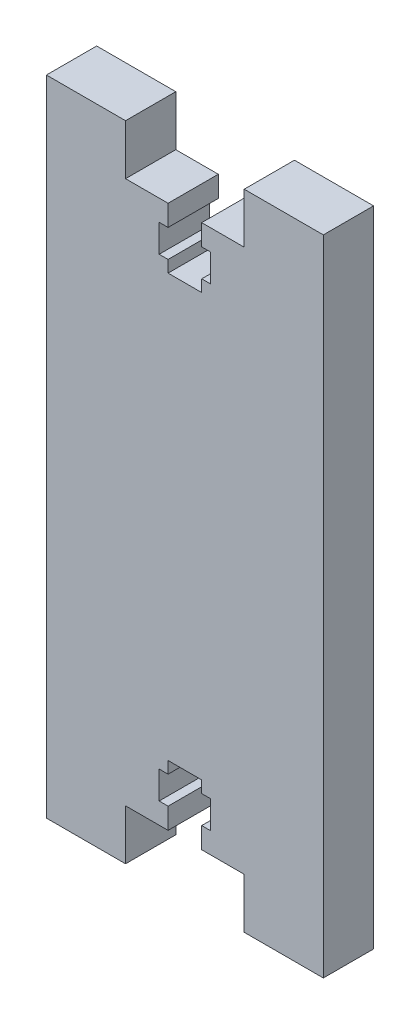
SolidWorks part; units mm, degrees
ref_plane "Front Plane" through (0, 0, 0) normal (0, 0, 1) x (1, 0, 0)
ref_plane "Top Plane" through (0, 0, 0) normal (0, 1, 0) x (1, 0, 0)
ref_plane "Right Plane" through (0, 0, 0) normal (1, 0, 0) x (0, 0, -1)
sketch "Sketch1" plane through (0, 0, 0) normal (0, 0, 1) x (1, 0, 0)
  line L0 (0, 0) -> (0, 23.0357) construction
  line L1 (-35, -68.65) -> (35, -68.65)
  line L2 (-35, -68.65) -> (-35, 68.65)
  line L3 (-35, 68.65) -> (35, 68.65)
  line L4 (35, -68.65) -> (35, 68.65)
  line L5 (-35, -68.65) -> (35, 68.65) construction
  line L6 (-35, 68.65) -> (35, -68.65) construction
  line L7 (-35, 68.65) -> (-15, 68.65)
  line L8 (-35, 68.65) -> (-35, 81.35)
  line L9 (-35, 81.35) -> (-15, 81.35)
  line L10 (-15, 68.65) -> (-15, 81.35)
  line L11 (0, 0) -> (16.6667, 0) construction
  line L12 (4.25, -56.35) -> (4.25, -53.35)
  line L13 (35, 68.65) -> (15, 68.65)
  line L14 (35, 68.65) -> (35, 81.35)
  line L15 (35, 81.35) -> (15, 81.35)
  line L16 (15, 68.65) -> (15, 81.35)
  line L17 (4.25, 68.65) -> (-4.25, 68.65)
  line L18 (4.25, 68.65) -> (4.25, 63.35)
  line L19 (4.25, 63.35) -> (-4.25, 63.35)
  line L20 (-4.25, 68.65) -> (-4.25, 63.35)
  line L21 (-6.5, 63.35) -> (6.5, 63.35)
  line L22 (-6.5, 63.35) -> (-6.5, 56.35)
  line L23 (-6.5, 56.35) -> (6.5, 56.35)
  line L24 (6.5, 63.35) -> (6.5, 56.35)
  line L29 (-4.25, 56.35) -> (4.25, 56.35)
  line L30 (-4.25, 56.35) -> (-4.25, 53.35)
  line L31 (-4.25, 53.35) -> (4.25, 53.35)
  line L32 (4.25, 56.35) -> (4.25, 53.35)
  line L33 (-4.25, -53.35) -> (4.25, -53.35)
  line L34 (-4.25, -56.35) -> (-4.25, -53.35)
  line L35 (-4.25, -56.35) -> (4.25, -56.35)
  line L36 (6.5, -63.35) -> (6.5, -56.35)
  line L37 (-6.5, -56.35) -> (6.5, -56.35)
  line L38 (-6.5, -63.35) -> (-6.5, -56.35)
  line L39 (-6.5, -63.35) -> (6.5, -63.35)
  line L40 (-4.25, -68.65) -> (-4.25, -63.35)
  line L41 (4.25, -63.35) -> (-4.25, -63.35)
  line L42 (4.25, -68.65) -> (4.25, -63.35)
  line L43 (4.25, -68.65) -> (-4.25, -68.65)
  line L44 (15, -68.65) -> (15, -81.35)
  line L45 (35, -81.35) -> (15, -81.35)
  line L46 (35, -68.65) -> (35, -81.35)
  line L47 (35, -68.65) -> (15, -68.65)
  line L48 (-15, -68.65) -> (-15, -81.35)
  line L49 (-35, -81.35) -> (-15, -81.35)
  line L50 (-35, -68.65) -> (-35, -81.35)
  line L51 (-35, -68.65) -> (-15, -68.65)
  point P0 (0, 0)
  point P28 (0, 56.35)
  point P29 (0, 63.35)
  point P30 (0, 63.35)
  point P31 (0, 56.35)
  point P32 (0, 53.35)
  point P33 (-35, 75)
  point P34 (-35, -75)
  dimension "D1" = 30
  dimension "D2" = 20
  dimension "D3" = 12.7
  dimension "D4" = 13
  dimension "D5" = 7
  dimension "D6" = 3
  dimension "D7" = 25
  dimension "D8" = 8.5
  dimension "D9" = 150
extrude "Boss-Extrude1" add sketch "Sketch1" along normal mid plane 12.7 contours L42 L1 L4 L3 L18 L21 L24 L23 L32 L31 L30 L22 L20 L2 L40 L39 L38 L37 L34 L33 L12 L36 | L1 L50 L49 L48 | L46 L1 L44 L45 | L16 L3 L14 L15 | L3 L10 L9 L8
equation "\"BOTTLE_DIA\"=120MM"
equation "\"HDPE_THICK\"=0.5IN"
equation "\"D3@Sketch1\"=\"HDPE_THICK\""
equation "\"D1@Boss-Extrude1\"=\"HDPE_THICK\""
equation "\"SUPPORT_HEIGHT\"=150MM"
equation "\"FLOOR_CLEARANCE\"=120MM"
equation "\"D9@Sketch1\"=\"SUPPORT_HEIGHT\""
